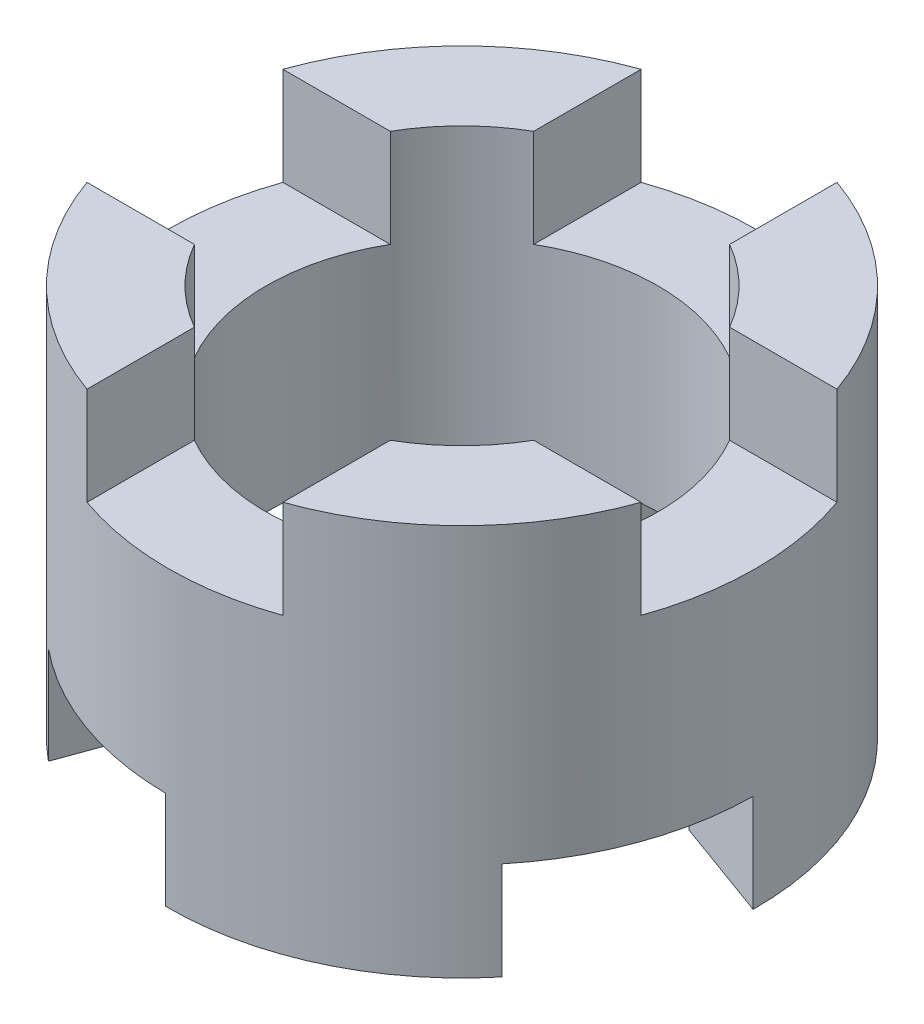
SolidWorks part; units mm, degrees
ref_plane "Front Plane" through (0, 0, 0) normal (0, 0, 1) x (1, 0, 0)
ref_plane "Top Plane" through (0, 0, 0) normal (0, 1, 0) x (1, 0, 0)
ref_plane "Right Plane" through (0, 0, 0) normal (1, 0, 0) x (0, 0, -1)
sketch "Sketch2" plane through (0, 0, 0) normal (0, 1, 0) x (1, 0, 0)
  circle A0 centre (0, 0) radius 19.05
  circle A1 centre (0, 0) radius 12.7
  dimension "D1" = 6.35
  dimension "D2" = 25.4
  dimension "D3" = 38.1
extrude "Boss-Extrude2" add sketch "Sketch2" along normal blind 25.4 contours A0 | A1
sketch "Sketch4" plane through (0, 25.4, 0) normal (0, 1, 0) x (1, 0, 0)
  line L1 (74.6776, 6.35) -> (-74.6776, 6.35)
  line L2 (74.6776, 6.35) -> (74.6776, -6.35)
  line L3 (74.6776, -6.35) -> (-74.6776, -6.35)
  line L4 (-74.6776, 6.35) -> (-74.6776, -6.35)
  line L5 (0, -6.35) -> (0, 6.35) construction
  line L6 (74.6776, 0) -> (-74.6776, 0) construction
  point P0 (0, 0)
  dimension "D1" = 12.7
extrude "Cut-Extrude7" cut sketch "Sketch4" against normal blind 6.35
pattern_circular "CirPattern1" count 2 every 90 about axis through (0, 25.4, 0) along (0, 1, 0) of "Cut-Extrude7"
sketch "Sketch8" plane through (0, 0, 0) normal (0, -1, 0) x (1, 0, 0)
  line L0 (-37.9043, -7.0385) -> (33.5606, 18.9726)
  line L1 (-37.9043, -7.0385) -> (-33.5606, -18.9726)
  line L2 (33.5606, 18.9726) -> (37.9043, 7.0385)
  line L3 (-33.5606, -18.9726) -> (37.9043, 7.0385)
  line L4 (-37.9043, -7.0385) -> (37.9043, 7.0385) construction
  line L5 (33.5606, 18.9726) -> (-33.5606, -18.9726) construction
  point P1 (0, 0)
  dimension "D1" = 12.7
extrude "Cut-Extrude9" cut sketch "Sketch8" against normal blind 6.35 contours L3 L2 L0 L1
pattern_circular "CirPattern2" count 2 every 90 about axis through (0, 0, 0) along (0, 1, 0) of "Cut-Extrude9"
equation "\"D1@Sketch4\"=\"D1@Sketch8\""
